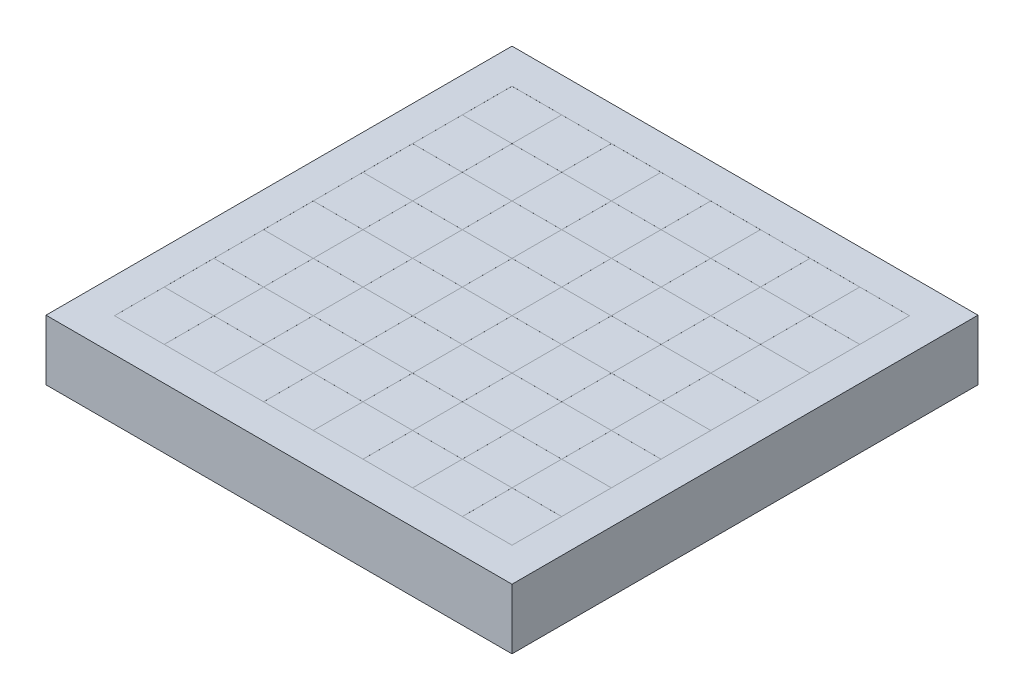
SolidWorks part; units mm, degrees
material "Mahogany"
ref_plane "Front Plane" through (0, 0, 0) normal (0, 0, 1) x (1, 0, 0)
ref_plane "Top Plane" through (0, 0, 0) normal (0, 1, 0) x (1, 0, 0)
ref_plane "Right Plane" through (0, 0, 0) normal (1, 0, 0) x (0, 0, -1)
sketch "Sketch1" plane through (0, 0, 0) normal (0, 1, 0) x (1, 0, 0)
  line L1 (-127.5, 127.5) -> (127.5, 127.5)
  line L2 (-127.5, 127.5) -> (-127.5, -127.5)
  line L3 (-127.5, -127.5) -> (127.5, -127.5)
  line L4 (127.5, 127.5) -> (127.5, -127.5)
  line L5 (-127.5, 127.5) -> (127.5, -127.5) construction
  line L6 (-127.5, -127.5) -> (127.5, 127.5) construction
  point P0 (0, 0)
  dimension "D1" = 255
extrude "Boss-Extrude1" add sketch "Sketch1" along normal blind 33
sketch "Sketch2" plane through (0, 33, 0) normal (0, 1, 0) x (1, 0, 0)
  line L0 (-127.5, 127.5) -> (-127.5, -127.5) construction
  line L1 (-108.5, 108.5) -> (-81.314, 108.5)
  line L2 (-108.5, 108.5) -> (-108.5, 81.314)
  line L3 (-108.5, 81.314) -> (-81.314, 81.314)
  line L4 (-81.314, 108.5) -> (-81.314, 81.314)
  line L5 (127.5, 127.5) -> (-127.5, 127.5) construction
  line L6 (-54.124, 108.5) -> (-26.9381, 108.5)
  line L7 (-54.124, 108.5) -> (-54.124, 81.314)
  line L8 (-26.9381, 108.5) -> (-26.9381, 81.314)
  line L9 (-54.124, 81.314) -> (-26.9381, 81.314)
  line L10 (0.2519, 108.5) -> (27.4379, 108.5)
  line L11 (0.2519, 108.5) -> (0.2519, 81.314)
  line L12 (27.4379, 108.5) -> (27.4379, 81.314)
  line L13 (0.2519, 81.314) -> (27.4379, 81.314)
  line L14 (54.6279, 108.5) -> (81.8138, 108.5)
  line L15 (54.6279, 108.5) -> (54.6279, 81.314)
  line L16 (81.8138, 108.5) -> (81.8138, 81.314)
  line L17 (54.6279, 81.314) -> (81.8138, 81.314)
  line L18 (-54.124, 54.124) -> (-26.9381, 54.124)
  line L19 (-54.124, 54.124) -> (-54.124, 26.9381)
  line L20 (-26.9381, 54.124) -> (-26.9381, 26.9381)
  line L21 (-54.124, 26.9381) -> (-26.9381, 26.9381)
  line L22 (0.2519, 54.124) -> (27.4379, 54.124)
  line L23 (0.2519, 54.124) -> (0.2519, 26.9381)
  line L24 (27.4379, 54.124) -> (27.4379, 26.9381)
  line L25 (0.2519, 26.9381) -> (27.4379, 26.9381)
  line L26 (54.6279, 54.124) -> (81.8138, 54.124)
  line L27 (54.6279, 54.124) -> (54.6279, 26.9381)
  line L28 (81.8138, 54.124) -> (81.8138, 26.9381)
  line L29 (54.6279, 26.9381) -> (81.8138, 26.9381)
  line L30 (-54.124, -0.2519) -> (-26.9381, -0.2519)
  line L31 (-54.124, -0.2519) -> (-54.124, -27.4379)
  line L32 (-26.9381, -0.2519) -> (-26.9381, -27.4379)
  line L33 (-54.124, -27.4379) -> (-26.9381, -27.4379)
  line L34 (0.2519, -0.2519) -> (27.4379, -0.2519)
  line L35 (0.2519, -0.2519) -> (0.2519, -27.4379)
  line L36 (27.4379, -0.2519) -> (27.4379, -27.4379)
  line L37 (0.2519, -27.4379) -> (27.4379, -27.4379)
  line L38 (54.6279, -0.2519) -> (81.8138, -0.2519)
  line L39 (54.6279, -0.2519) -> (54.6279, -27.4379)
  line L40 (81.8138, -0.2519) -> (81.8138, -27.4379)
  line L41 (54.6279, -27.4379) -> (81.8138, -27.4379)
  line L42 (-54.124, -54.6279) -> (-26.9381, -54.6279)
  line L43 (-54.124, -54.6279) -> (-54.124, -81.8138)
  line L44 (-26.9381, -54.6279) -> (-26.9381, -81.8138)
  line L45 (-54.124, -81.8138) -> (-26.9381, -81.8138)
  line L46 (0.2519, -54.6279) -> (27.4379, -54.6279)
  line L47 (0.2519, -54.6279) -> (0.2519, -81.8138)
  line L48 (27.4379, -54.6279) -> (27.4379, -81.8138)
  line L49 (0.2519, -81.8138) -> (27.4379, -81.8138)
  line L50 (54.6279, -54.6279) -> (81.8138, -54.6279)
  line L51 (54.6279, -54.6279) -> (54.6279, -81.8138)
  line L52 (81.8138, -54.6279) -> (81.8138, -81.8138)
  line L53 (54.6279, -81.8138) -> (81.8138, -81.8138)
  line L54 (-108.5, 54.124) -> (-81.314, 54.124)
  line L55 (-108.5, 54.124) -> (-108.5, 26.9381)
  line L56 (-81.314, 54.124) -> (-81.314, 26.9381)
  line L57 (-108.5, 26.9381) -> (-81.314, 26.9381)
  line L58 (-108.5, -0.2519) -> (-81.314, -0.2519)
  line L59 (-108.5, -0.2519) -> (-108.5, -27.4379)
  line L60 (-81.314, -0.2519) -> (-81.314, -27.4379)
  line L61 (-108.5, -27.4379) -> (-81.314, -27.4379)
  line L62 (-108.5, -54.6279) -> (-81.314, -54.6279)
  line L63 (-108.5, -54.6279) -> (-108.5, -81.8138)
  line L64 (-81.314, -54.6279) -> (-81.314, -81.8138)
  line L65 (-108.5, -81.8138) -> (-81.314, -81.8138)
  line L66 (-108.5, 127.5) -> (-108.5, -127.5) construction
  line L67 (-127.5, -127.5) -> (127.5, -127.5) construction
  line L68 (-26.93, 81.31) -> (0.26, 81.31)
  line L69 (-81.31, 81.31) -> (-54.12, 81.31)
  line L70 (-81.31, 81.31) -> (-81.31, 54.12)
  line L71 (-81.31, 54.12) -> (-54.12, 54.12)
  line L72 (-54.12, 81.31) -> (-54.12, 54.12)
  line L73 (-26.93, 81.31) -> (-26.93, 54.12)
  line L74 (0.26, 81.31) -> (0.26, 54.12)
  line L75 (-26.93, 54.12) -> (0.26, 54.12)
  line L76 (27.45, 81.31) -> (54.64, 81.31)
  line L77 (27.45, 81.31) -> (27.45, 54.12)
  line L78 (54.64, 81.31) -> (54.64, 54.12)
  line L79 (27.45, 54.12) -> (54.64, 54.12)
  line L80 (81.83, 81.31) -> (109.02, 81.31)
  line L81 (81.83, 81.31) -> (81.83, 54.12)
  line L82 (109.02, 81.31) -> (109.02, 54.12)
  line L83 (81.83, 54.12) -> (109.02, 54.12)
  line L84 (-26.93, 26.93) -> (0.26, 26.93)
  line L85 (-26.93, 26.93) -> (-26.93, -0.26)
  line L86 (0.26, 26.93) -> (0.26, -0.26)
  line L87 (-26.93, -0.26) -> (0.26, -0.26)
  line L88 (27.45, 26.93) -> (54.64, 26.93)
  line L89 (27.45, 26.93) -> (27.45, -0.26)
  line L90 (54.64, 26.93) -> (54.64, -0.26)
  line L91 (27.45, -0.26) -> (54.64, -0.26)
  line L92 (81.83, 26.93) -> (109.02, 26.93)
  line L93 (81.83, 26.93) -> (81.83, -0.26)
  line L94 (109.02, 26.93) -> (109.02, -0.26)
  line L95 (81.83, -0.26) -> (109.02, -0.26)
  line L96 (-26.93, -27.45) -> (0.26, -27.45)
  line L97 (-26.93, -27.45) -> (-26.93, -54.64)
  line L98 (0.26, -27.45) -> (0.26, -54.64)
  line L99 (-26.93, -54.64) -> (0.26, -54.64)
  line L100 (27.45, -27.45) -> (54.64, -27.45)
  line L101 (27.45, -27.45) -> (27.45, -54.64)
  line L102 (54.64, -27.45) -> (54.64, -54.64)
  line L103 (27.45, -54.64) -> (54.64, -54.64)
  line L104 (81.83, -27.45) -> (109.02, -27.45)
  line L105 (81.83, -27.45) -> (81.83, -54.64)
  line L106 (109.02, -27.45) -> (109.02, -54.64)
  line L107 (81.83, -54.64) -> (109.02, -54.64)
  line L108 (-26.93, -81.83) -> (0.26, -81.83)
  line L109 (-26.93, -81.83) -> (-26.93, -109.02)
  line L110 (0.26, -81.83) -> (0.26, -109.02)
  line L111 (-26.93, -109.02) -> (0.26, -109.02)
  line L112 (27.45, -81.83) -> (54.64, -81.83)
  line L113 (27.45, -81.83) -> (27.45, -109.02)
  line L114 (54.64, -81.83) -> (54.64, -109.02)
  line L115 (27.45, -109.02) -> (54.64, -109.02)
  line L116 (81.83, -81.83) -> (109.02, -81.83)
  line L117 (81.83, -81.83) -> (81.83, -109.02)
  line L118 (109.02, -81.83) -> (109.02, -109.02)
  line L119 (81.83, -109.02) -> (109.02, -109.02)
  line L120 (-81.31, 26.93) -> (-54.12, 26.93)
  line L121 (-81.31, 26.93) -> (-81.31, -0.26)
  line L122 (-54.12, 26.93) -> (-54.12, -0.26)
  line L123 (-81.31, -0.26) -> (-54.12, -0.26)
  line L124 (-81.31, -27.45) -> (-54.12, -27.45)
  line L125 (-81.31, -27.45) -> (-81.31, -54.64)
  line L126 (-54.12, -27.45) -> (-54.12, -54.64)
  line L127 (-81.31, -54.64) -> (-54.12, -54.64)
  line L128 (-81.31, -81.83) -> (-54.12, -81.83)
  line L129 (-81.31, -81.83) -> (-81.31, -109.02)
  line L130 (-54.12, -81.83) -> (-54.12, -109.02)
  line L131 (-81.31, -109.02) -> (-54.12, -109.02)
  line M65 (127.5, -127.5) -> (127.5, 127.5)
  line M66 (127.5, 127.5) -> (-127.5, 127.5)
  line M67 (-127.5, 127.5) -> (-127.5, -127.5)
  line M68 (-127.5, -127.5) -> (127.5, -127.5)
  dimension "D1" = 27.186
  dimension "D2" = 19
  dimension "D3" = 19
  dimension "D6" = 27.19
  dimension "D7" = 27.19
  dimension "D8" = 27.19
  dimension "D9" = 27.19
  dimension "D10" = 27.19
  dimension "D11" = 4
  dimension "D13" = 18.48
  dimension "D14" = 27.19
  dimension "D15" = 27.19
  dimension "D4" = 4
  dimension "D5" = 4
  dimension "D12" = 4
extrude "Boss-Extrude3" add sketch "Sketch2" along normal blind 0.02 contours L66 L1 L4 L3 L54 L56 L57 L58 L60 L61 L62 L64 L65 L131 L129 L128 L130 L127 L125 L124 L126 L42 L44 L45 L43 L123 L121 L120 L122 L30 L32 L33 L31 L119 L117 L116 L118 L115 L113 M66 M68 M65 | L66 L63 L59 L55 L2 M66 M67 M68 | L38 L40 L41 L39
sketch "Sketch3" plane through (0, 33.02, 0) normal (0, 1, 0) x (1, 0, 0)
  line L1 (-108.5, 108.5) -> (109.02, 108.5)
  line L2 (-108.5, 108.5) -> (-108.5, -109.02)
  line L3 (-108.5, -109.02) -> (109.02, -109.02)
  line L4 (109.02, 108.5) -> (109.02, -109.02)
extrude "Cut-Extrude4" cut sketch "Sketch3" against normal blind 0.01
